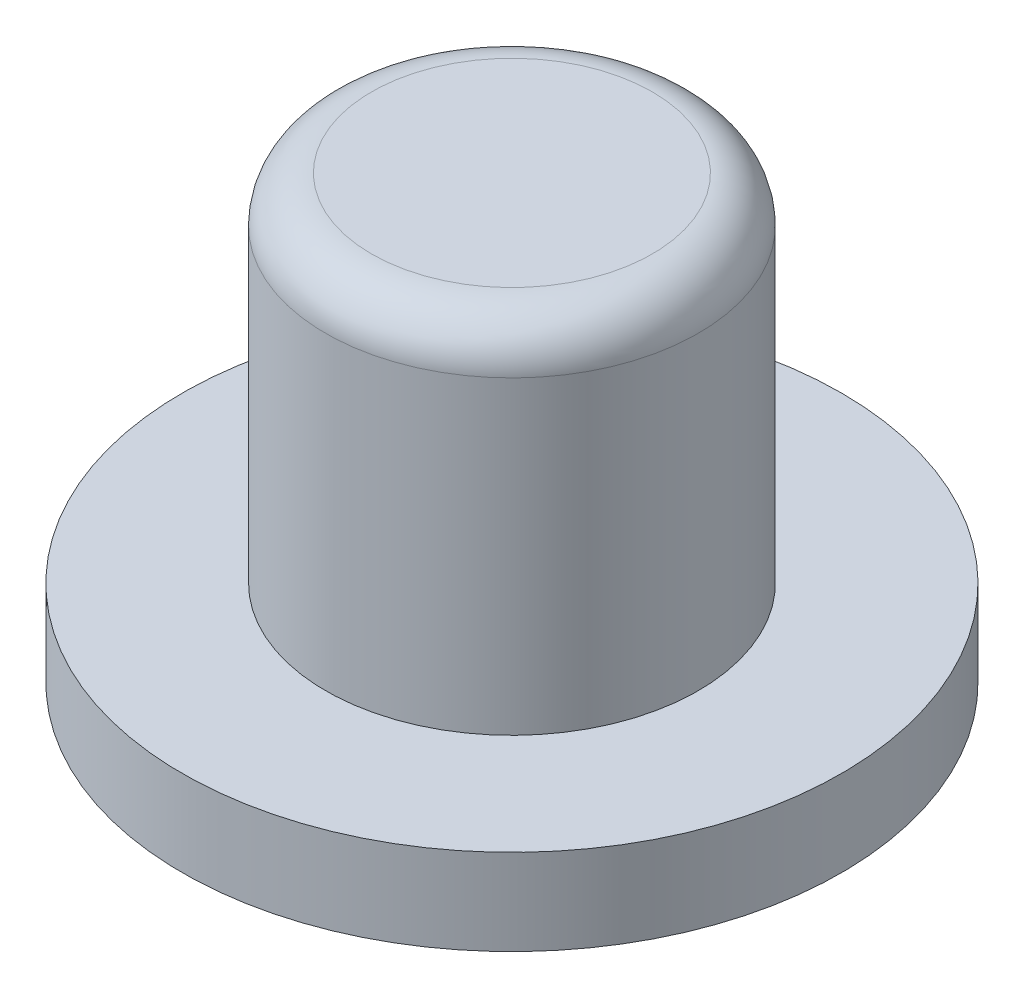
SolidWorks part; units mm, degrees
ref_plane "Front" through (0, 0, 0) normal (0, 0, 1) x (1, 0, 0)
ref_plane "Top" through (0, 0, 0) normal (0, 1, 0) x (1, 0, 0)
ref_plane "Right" through (0, 0, 0) normal (1, 0, 0) x (0, 0, -1)
sketch "Sketch1" plane through (0, 0, 0) normal (0, 0, 1) x (1, 0, 0)
  line L0 (0, 0) -> (0, 8) construction
  line L2 (-5.75, 0.3) -> (-5.75, 1.8)
  line L3 (-5.75, 1.8) -> (-3.25, 1.8)
  line L4 (-3.25, 1.8) -> (-3.25, 8)
  line L5 (-3.25, 8) -> (0, 8)
  line L6 (0, 8) -> (0, 0)
  arc A0 (-5.75, 0.3) -> (0, 0) centre (-1.0576, 34.984) ccw
  dimension "D4" = 1.5
  dimension "D5" = 35
  dimension "D1" = 8
  dimension "D2" = 3.25
  dimension "D3" = 6.2
  dimension "D6" = 2.5
revolve "Revolve1" add sketch "Sketch1" angle 360 about L0
fillet "Fillet1" radius 0.8 1 edges at (0, 8, -3.25)
